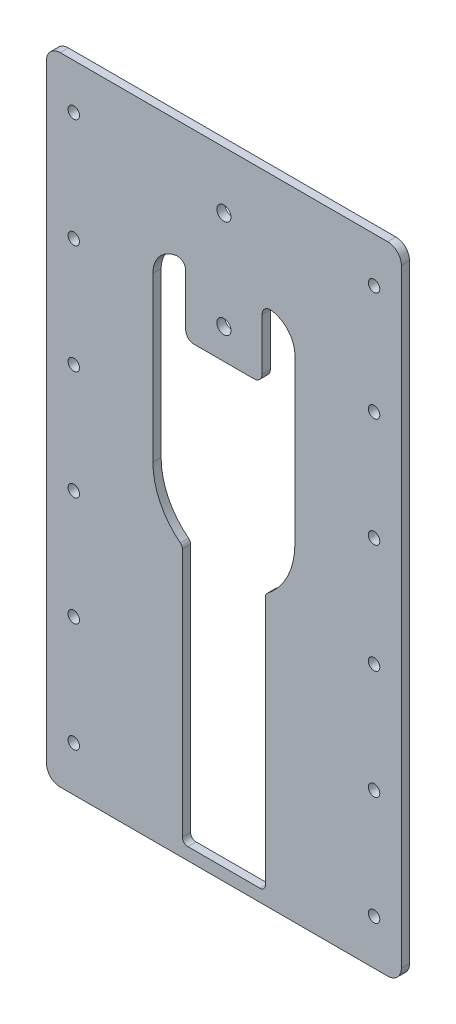
SolidWorks part; units mm, degrees
material "Thornel Mat VMA"
ref_plane "Front Plane" through (0, 0, 0) normal (0, 0, 1) x (1, 0, 0)
ref_plane "Top Plane" through (0, 0, 0) normal (0, 1, 0) x (1, 0, 0)
ref_plane "Right Plane" through (0, 0, 0) normal (1, 0, 0) x (0, 0, -1)
sketch "Sketch1" plane through (0, 0, 0) normal (0, 0, 1) x (1, 0, 0)
  line L1 (-65, -126.5) -> (65, -126.5)
  line L2 (-65, -126.5) -> (-65, 126.5)
  line L3 (-65, 126.5) -> (65, 126.5)
  line L4 (65, -126.5) -> (65, 126.5)
  line L5 (-65, -126.5) -> (65, 126.5) construction
  line L6 (-65, 126.5) -> (65, -126.5) construction
  line L7 (-65, 126.5) -> (-42, 126.5)
  line L8 (-65, 126.5) -> (-65, 106.5)
  line L9 (-65, 106.5) -> (-42, 106.5)
  line L10 (-42, 126.5) -> (-42, 106.5)
  point P0 (0, 0)
  dimension "D1" = 130
  dimension "D2" = 253
  dimension "D3" = 23
  dimension "D4" = 20
extrude "Boss-Extrude1" add sketch "Sketch1" along normal blind 3 contours L3 L10 L9 L2 L1 L4
sketch "Sketch2" plane through (0, 0, 3) normal (0, 0, 1) x (1, 0, 0)
  line L5 (65, -126.5) -> (65, 126.5) construction
  line L6 (-42, 126.5) -> (65, 126.5)
  line L7 (-42, 126.5) -> (-42, 106.5)
  line L8 (-42, 106.5) -> (65, 106.5)
  line L9 (65, 126.5) -> (65, 106.5)
  line L10 (-65, 106.5) -> (-42, 106.5) construction
extrude "Cut-Extrude1" cut sketch "Sketch2" against normal through all
sketch "Sketch3" plane through (0, 0, 0) normal (0, 0, -1) x (-1, 0, 0)
  line L0 (0, -126.5) -> (0, -6.5) construction
  line L1 (65, -126.5) -> (-65, -126.5) construction
  circle A0 centre (0, -6.5) radius 26
  dimension "D2" = 52
  dimension "D1" = 120
extrude "Cut-Extrude2" cut sketch "Sketch3" against normal through all
fillet "Fillet1" radius 5 4 edges at (-65, -126.5, 1.5) (-65, 106.5, 1.5) (65, 106.5, 1.5) (65, -126.5, 1.5)
sketch "Sketch4" plane through (0, 0, 3) normal (0, 0, 1) x (1, 0, 0)
  line L0 (0, -5.6801) -> (0, -122) construction
  line L1 (-60, -126.5) -> (60, -126.5) construction
  line L2 (-15.2, -5.6801) -> (-15.2, -122)
  line L3 (15.2, -5.6801) -> (15.2, -122)
  line L4 (-15.2, -5.6801) -> (15.2, -5.6801)
  line L5 (-15.2, -122) -> (15.2, -122)
  dimension "D1" = 4.5
  dimension "D2" = 15.2
  dimension "D3" = 15.2
extrude "Cut-Extrude3" cut sketch "Sketch4" against normal through all
sketch "Sketch5" plane through (0, 0, 0) normal (0, 0, -1) x (-1, 0, 0)
  line L0 (0, -6.5) -> (-65, -6.5) construction
  line L1 (-65, -121.5) -> (-65, 101.5) construction
  line L3 (-26, -6.5) -> (26, -6.5)
  line L4 (-26, -6.5) -> (-26, 63.5)
  line L5 (-26, 63.5) -> (26, 63.5)
  line L6 (26, -6.5) -> (26, 63.5)
  dimension "D1" = 52
  dimension "D2" = 70
extrude "Cut-Extrude4" cut sketch "Sketch5" against normal through all
fillet "Fillet2" radius 10 2 edges at (-26, 63.5, 1.5) (26, 63.5, 1.5)
fillet "Fillet3" radius 2 4 edges at (15.2, -27.5941, 1.5) (-15.2, -122, 1.5) (-15.2, -27.5941, 1.5) (15.2, -122, 1.5)
sketch "Sketch6" plane through (0, 0, 0) normal (0, 0, -1) x (-1, 0, 0)
  line L0 (16, 63.5) -> (-16, 63.5) construction
  line L1 (-14, 38.5) -> (14, 38.5)
  line L2 (-14, 38.5) -> (-14, 88.5)
  line L3 (-14, 88.5) -> (14, 88.5)
  line L4 (14, 38.5) -> (14, 88.5)
  line L5 (-14, 38.5) -> (14, 88.5) construction
  line L6 (-14, 88.5) -> (14, 38.5) construction
  point P0 (0, 63.5)
  dimension "D1" = 28
  dimension "D2" = 50
extrude "Boss-Extrude2" add sketch "Sketch6" against normal up to surface (3 mm away) up to face at (0, -26.6463, 3)
fillet "Fillet4" radius 3 4 edges at (14, 38.5, 1.5) (-14, 38.5, 1.5) (-14, 63.5, 1.5) (14, 63.5, 1.5)
sketch "Sketch7" plane through (0, 0, 0) normal (0, 0, -1) x (-1, 0, 0)
  line L0 (-55, 106.5) -> (-55, -126.5) construction
  line L1 (60, 106.5) -> (-60, 106.5) construction
  line L2 (60, -126.5) -> (-60, -126.5) construction
  line L3 (-65, -121.5) -> (-65, 101.5) construction
  circle A0 centre (-55, 90) radius 2.1
  circle A1 centre (-55, 50) radius 2.1
  circle A2 centre (-55, 10) radius 2.1
  circle A3 centre (-55, -30) radius 2.1
  circle A4 centre (-55, -70) radius 2.1
  circle A5 centre (-55, -110) radius 2.1
  dimension "D2" = 16.5
  dimension "D3" = 4.2
  dimension "D1" = 10
  dimension "D5" = 40
  dimension "D4" = 6
extrude "Cut-Extrude5" cut sketch "Sketch7" against normal through all
mirror "Mirror1" about plane through (0, 0, 0) normal (1, 0, 0) of "Cut-Extrude5"
sketch "Sketch8" plane through (0, 0, 3) normal (0, 0, 1) x (1, 0, 0)
  circle A0 centre (0, 49.5699) radius 2.6
  circle A1 centre (0, 85.5699) radius 2.6
  dimension "D1" = 5.2
extrude "Cut-Extrude6" cut sketch "Sketch8" against normal through all
